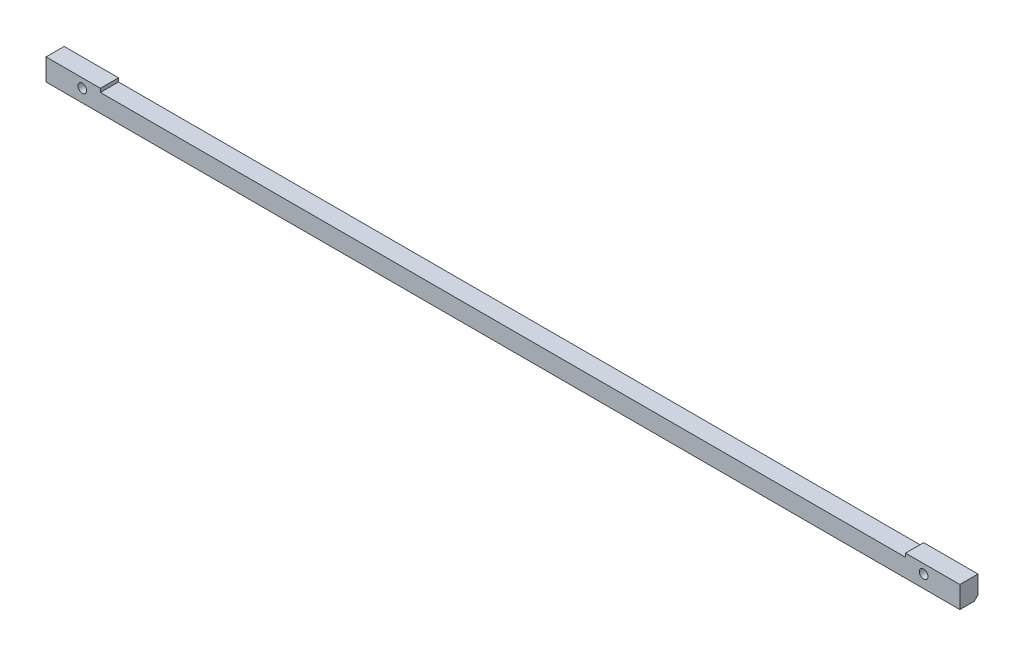
SolidWorks part; units mm, degrees
material "Д16Т ГОСТ 4784-74"
ref_plane "Спереди" through (0, 0, 0) normal (0, 0, 1) x (1, 0, 0)
ref_plane "Сверху" through (0, 0, 0) normal (0, 1, 0) x (1, 0, 0)
ref_plane "Справа" through (0, 0, 0) normal (1, 0, 0) x (0, 0, -1)
sketch "Эскиз1" plane through (0, 0, 0) normal (0, 0, 1) x (1, 0, 0)
  line L0 (0, 0) -> (0, 31.2218) construction
  line L1 (-126, 0) -> (126, 0)
  line L2 (126, 0) -> (126, 6)
  line L3 (126, 6) -> (111, 6)
  line L4 (111, 6) -> (111, 5)
  line L5 (111, 5) -> (-111, 5)
  line L6 (-111, 6) -> (-111, 5)
  line L7 (-126, 6) -> (-111, 6)
  line L8 (-126, 0) -> (-126, 6)
  point P9 (0, 5)
  dimension "D1" = 6
  dimension "D2" = 15
  dimension "D3" = 222
  dimension "D4" = 5
extrude "Бобышка-Вытянуть1" add sketch "Эскиз1" along normal blind 5
chamfer "Фаска1" distance 1 angle 45 1 edges at (0, 0, 0)
hole_wizard "Цековка для  винта с внутренним шестигранником M21" positions "Эскиз3" profile "Эскиз2" counterbore size "M2" standard "DIN" end condition through all
sketch "Эскиз3" plane through (0, 0, 0) normal (0, 0, -1) x (-1, 0, 0)
  line L0 (126, 6) -> (126, 1) construction
  line L1 (111, 6) -> (126, 6) construction
  line L2 (-126, 1) -> (-126, 6) construction
  line L3 (-126, 6) -> (-111, 6) construction
  point P0 (-116, 3.5)
  point P1 (116, 3.5)
  dimension "D1" = 10
  dimension "D2" = 2.5
  dimension "D3" = 10
  dimension "D4" = 2.5
sketch "Эскиз2" plane through (116, 3.5, 0) normal (1, 0, 0) x (0, 1, 0)
  line L0 (0, 0) -> (0, 5)
  line L1 (0, 5) -> (1.2, 5)
  line L3 (1.2, 5) -> (1.2, 2.9)
  line L4 (1.2, 2.9) -> (2.2, 2.9)
  line L5 (2.2, 2.9) -> (2.2, 0)
  line L7 (2.2, 0) -> (0, 0)
  line L11 (0, -6.35) -> (0, 107.95) construction
  dimension "Диаметр сквозного отверстия" = 2.4
  dimension "Глубина сквозного отверстия" = 5
  dimension "Диаметр цековки" = 4.4
  dimension "Глубина цековки" = 2.9
